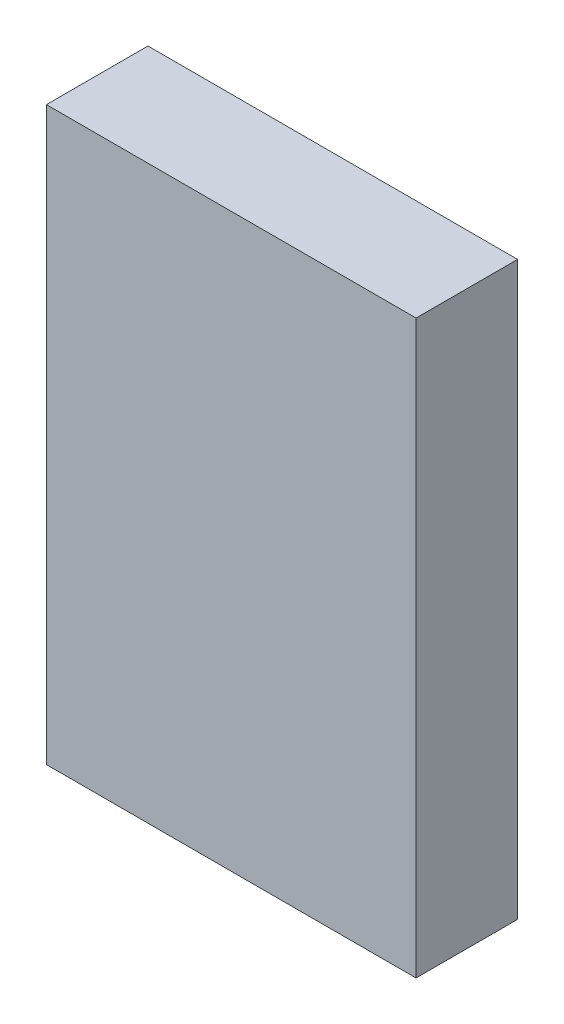
SolidWorks part; units mm, degrees
ref_plane "Plano frontal" through (0, 0, 0) normal (0, 0, 1) x (1, 0, 0)
ref_plane "Plano superior" through (0, 0, 0) normal (0, 1, 0) x (1, 0, 0)
ref_plane "Plano direito" through (0, 0, 0) normal (1, 0, 0) x (0, 0, -1)
other "Centro da massa"
sketch "Esboço1" plane through (0, 0, 0) normal (0, 0, 1) x (1, 0, 0)
  line L1 (43.94, 67.945) -> (-43.94, 67.945)
  line L2 (43.94, 67.945) -> (43.94, -67.945)
  line L3 (43.94, -67.945) -> (-43.94, -67.945)
  line L4 (-43.94, 67.945) -> (-43.94, -67.945)
  line L5 (43.94, 67.945) -> (-43.94, -67.945) construction
  line L6 (43.94, -67.945) -> (-43.94, 67.945) construction
  point P0 (0, 0)
  dimension "D1" = 87.88
  dimension "D2" = 135.89
extrude "Ressalto-extrusão1" add sketch "Esboço1" along normal blind 24.14
